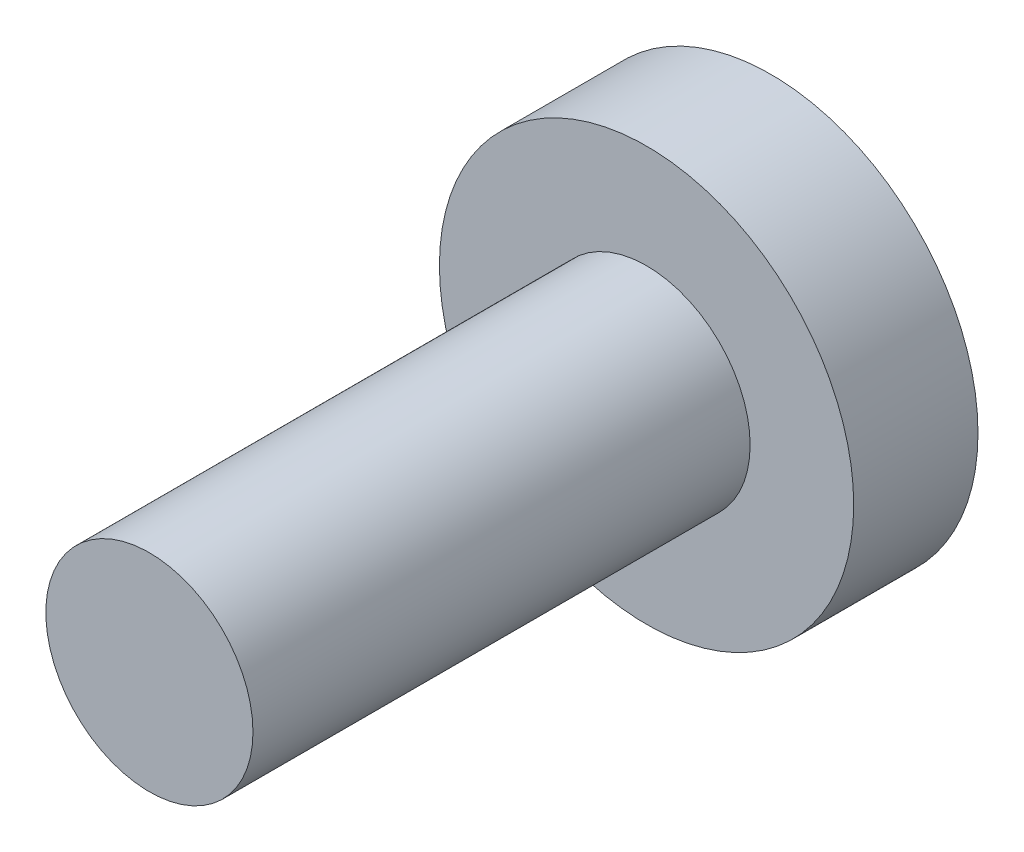
SolidWorks part; units mm, degrees
ref_plane "前视基准面" through (0, 0, 0) normal (0, 0, 1) x (1, 0, 0)
ref_plane "上视基准面" through (0, 0, 0) normal (0, 1, 0) x (1, 0, 0)
ref_plane "右视基准面" through (0, 0, 0) normal (1, 0, 0) x (0, 0, -1)
sketch "草图1" plane through (0, 0, 0) normal (0, 0, 1) x (1, 0, 0)
  circle A0 centre (0, 0) radius 1.25
extrude "凸台-拉伸1" add sketch "草图1" along normal blind 6
sketch "草图2" plane through (0, 0, 0) normal (0, 0, -1) x (-1, 0, 0)
  circle A0 centre (0, 0) radius 2.5
extrude "凸台-拉伸2" add sketch "草图2" along normal blind 1.5
sketch "草图3" plane through (0, 0, -1.5) normal (0, 0, -1) x (-1, 0, 0)
  line L0 (-2.5, 0) -> (2.5, 0) construction
  line L1 (0, -2.5) -> (0, 2.5) construction
  line L2 (0.18, 1.25) -> (0.18, 0.18)
  line L3 (-1.25, 0.18) -> (-0.18, 0.18)
  line L4 (-1.25, 0.18) -> (-1.25, -0.18)
  line L5 (-1.25, -0.18) -> (-0.18, -0.18)
  line L6 (1.25, 0.18) -> (1.25, -0.18)
  line L7 (0, 0) -> (1.7678, -1.7678) construction
  line L8 (-0.18, -1.25) -> (0.18, -1.25)
  line L9 (-0.18, 1.25) -> (-0.18, 0.18)
  line L10 (-0.18, 1.25) -> (0.18, 1.25)
  line L11 (-0.18, -0.18) -> (-0.18, -1.25)
  line L12 (0.18, -0.18) -> (1.25, -0.18)
  line L13 (0.18, -0.18) -> (0.18, -1.25)
  line L14 (0.18, 0.18) -> (1.25, 0.18)
  circle A0 centre (0, 0) radius 2.5 construction
  point P6 (0, 0)
  point P10 (0, 0)
  dimension "D1" = 2.5
  dimension "D2" = 1.25
  dimension "D3" = 0.36
  dimension "D4" = 0.18
extrude "切除-拉伸1" cut sketch "草图3" against normal blind 0.5
